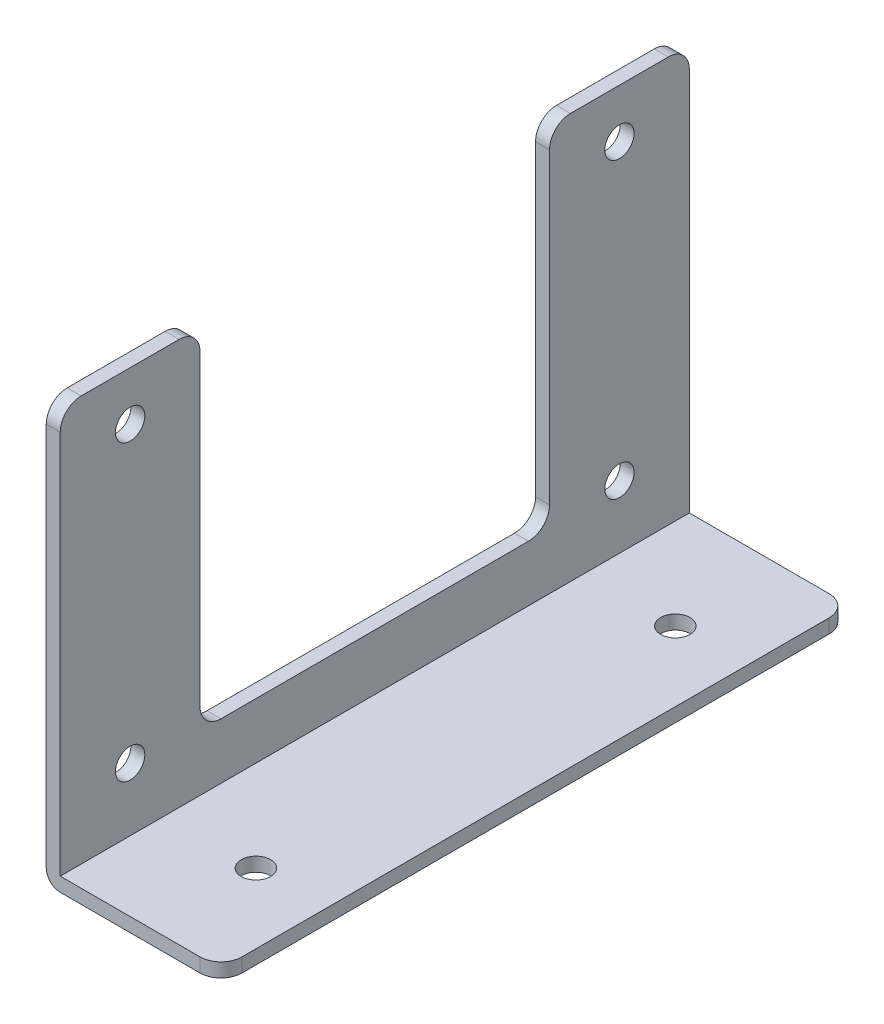
SolidWorks part; units mm, degrees
material "6061 合金"
ref_plane "正面" through (0, 0, 0) normal (0, 0, 1) x (1, 0, 0)
ref_plane "平面" through (0, 0, 0) normal (0, 1, 0) x (1, 0, 0)
ref_plane "右側面" through (0, 0, 0) normal (1, 0, 0) x (0, 0, -1)
sketch "ｽｹｯﾁ1" plane through (0, 0, 0) normal (0, 0, 1) x (1, 0, 0)
  line L1 (0, -39.5314) -> (2, -39.5314)
  line L2 (0, -39.5314) -> (0, -97.5314)
  line L3 (2, -99.5314) -> (25, -99.5314)
  line L4 (25, -97.5314) -> (25, -99.5314)
  line L6 (2, -39.5314) -> (2, -97.5314)
  line L7 (2, -97.5314) -> (25, -97.5314)
  arc A0 (0, -97.5314) -> (2, -99.5314) centre (2, -97.5314) ccw
  point P11 (0, -99.5314)
  dimension "D4" = 2
  dimension "D1" = 2
  dimension "D2" = 25
  dimension "D3" = 60
extrude "ﾎﾞｽ - 押し出し1" add sketch "ｽｹｯﾁ1" along normal mid plane 90
sketch "ｽｹｯﾁ2" plane through (0, 0, 0) normal (1, 0, 0) x (0, 0, -1)
  line L0 (-45, -39.5314) -> (45, -39.5314) construction
  line L1 (-25, -39.5314) -> (25, -39.5314)
  line L2 (-25, -39.5314) -> (-25, -89.5314)
  line L3 (-25, -89.5314) -> (25, -89.5314)
  line L4 (25, -39.5314) -> (25, -89.5314)
  line L5 (-45, -97.5314) -> (45, -97.5314) construction
  line L6 (-35, -39.5314) -> (-35, -99.5314) construction
  line L7 (0, -99.5314) -> (0, -39.5314) construction
  line L8 (-45, -99.5314) -> (45, -99.5314) construction
  line L9 (-45, -97.5314) -> (-45, -39.5314) construction
  line L10 (-35, -88.5314) -> (35, -88.5314) construction
  circle A0 centre (-35, -46.5314) radius 2.1
  circle A1 centre (-35, -88.5314) radius 2.1
  circle A2 centre (35, -88.5314) radius 2.1
  circle A3 centre (35, -46.5314) radius 2.1
  point P7 (0, -39.5314)
  point P8 (0, -39.5314)
  point P25 (0, 0)
  dimension "D4" = 4.2
  dimension "D7" = 42
  dimension "D1" = 50
  dimension "D2" = 8
  dimension "D3" = 10
  dimension "D5" = 7
  dimension "D6" = 11
extrude "ｶｯﾄ - 押し出し2" cut sketch "ｽｹｯﾁ2" along normal through all
sketch "ｽｹｯﾁ3" plane through (0, 0, 0) normal (0, 1, 0) x (1, 0, 0)
  line L0 (15, 45) -> (15, -45) construction
  line L1 (25, 45) -> (2, 45) construction
  line L2 (25, -45) -> (2, -45) construction
  line L3 (25, -45) -> (25, 45) construction
  line L4 (25, 0) -> (0, 0) construction
  line L5 (0, -25) -> (0, 25) construction
  circle A0 centre (15, 30) radius 2.1
  circle A1 centre (15, -30) radius 2.1
  dimension "D4" = 4.2
  dimension "D1" = 10
  dimension "D2" = 15
  dimension "D3" = 60
extrude "ｶｯﾄ - 押し出し3" cut sketch "ｽｹｯﾁ3" against normal through all
fillet "ﾌｨﾚｯﾄ1" radius 3 8 edges at (1, -89.5314, 25) (1, -89.5314, -25) (25, -98.5314, -45) (1, -39.5314, -45) (1, -39.5314, 45) (25, -98.5314, 45) (1, -39.5314, -25) (1, -39.5314, 25)
